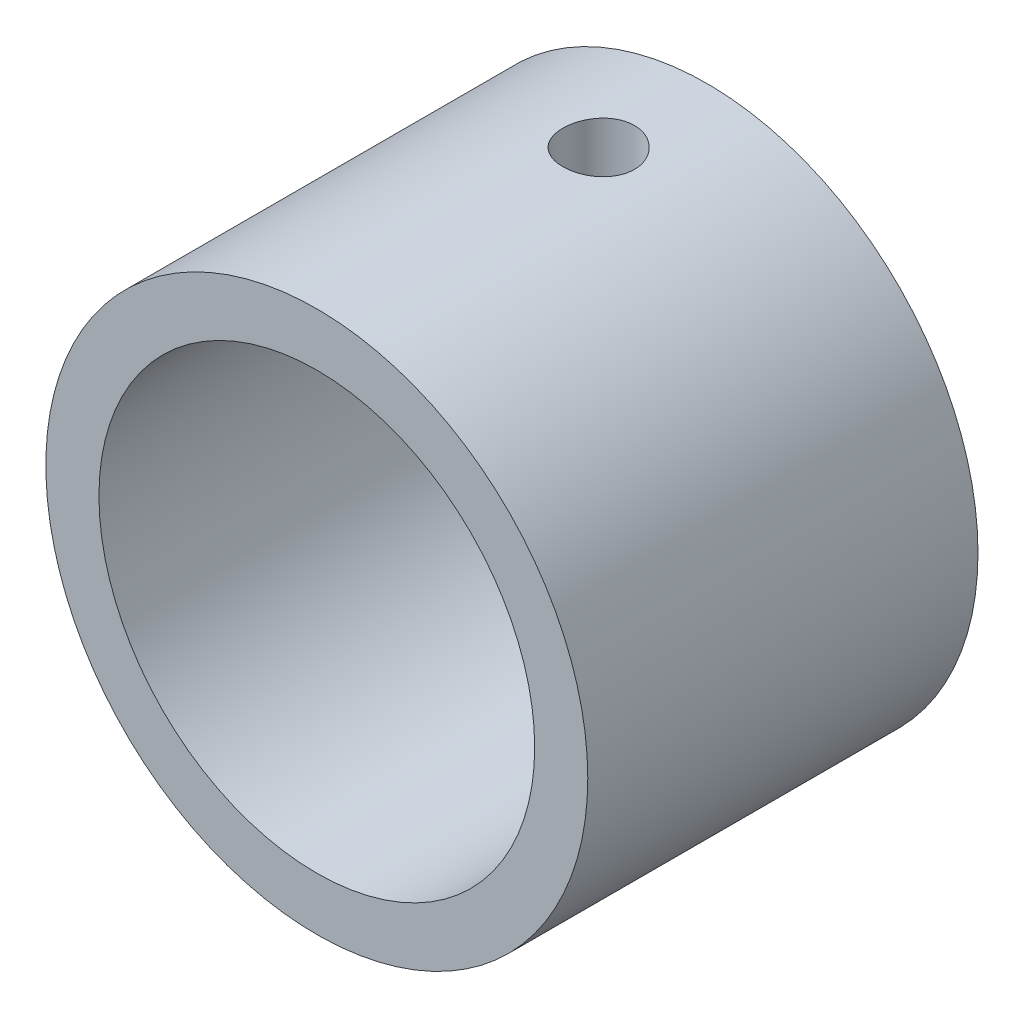
SolidWorks part; units mm, degrees
ref_plane "Front Plane" through (0, 0, 0) normal (0, 0, 1) x (1, 0, 0)
ref_plane "Top Plane" through (0, 0, 0) normal (0, 1, 0) x (1, 0, 0)
ref_plane "Right Plane" through (0, 0, 0) normal (1, 0, 0) x (0, 0, -1)
sketch "Sketch1" plane through (0, 0, 0) normal (0, 0, 1) x (1, 0, 0)
  circle A0 centre (0, 0) radius 12.5
  dimension "D1" = 25
extrude "Boss-Extrude1" add sketch "Sketch1" along normal blind 18
sketch "Sketch2" plane through (0, 0, 18) normal (0, 0, 1) x (1, 0, 0)
  circle A0 centre (0, 0) radius 10.05
  dimension "D1" = 20.1
extrude "Cut-Extrude1" cut sketch "Sketch2" against normal through all both and the other way through all contours A0
sketch "Sketch4" plane through (0, 0, 0) normal (1, 0, 0) x (0, 0, -1)
  line L0 (0, 0) -> (-20.812, 0) construction
sketch "Sketch5" plane through (0, 0, 0) normal (0, 0, 1) x (1, 0, 0)
  line L0 (14.984, 0) -> (0, 0) construction
  point P3 (0, 0)
ref_plane "Plane1" through (0, -12.5, 0) normal (0, -1, 0) x (-1, 0, 0)
sketch "Sketch6" plane through (0, -12.5, 0) normal (0, -1, 0) x (-1, 0, 0)
  line L0 (0, 0) -> (0, -20.812) construction
  line L1 (12.5, 0) -> (-12.5, 0) construction
  circle A0 centre (0, -5) radius 1.65
  point P4 (0, 0)
  point P5 (0, 0)
  dimension "D2" = 3.3
  dimension "D1" = 5
extrude "Cut-Extrude2" cut sketch "Sketch6" against normal through all both
ref_plane "Plane2" through (12.5, 0, 0) normal (1, 0, 0) x (0, 0, -1)
sketch "Sketch7" plane through (12.5, 0, 0) normal (1, 0, 0) x (0, 0, -1)
  line L0 (0, 0) -> (-20.812, 0) construction
  line L1 (-18, 12.5) -> (-18, -12.5) construction
  circle A0 centre (-16, 0) radius 1.65
  point P2 (0, 0)
  dimension "D2" = 3.3
  dimension "D1" = 2
equation "\"D1@Sketch1\"=25"
